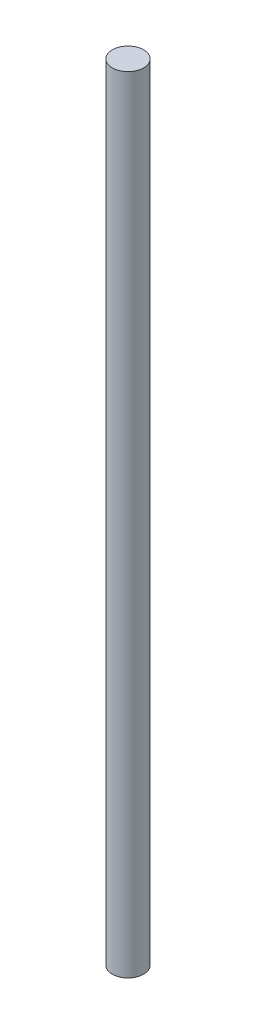
SolidWorks part; units mm, degrees
ref_plane "前视基准面" through (0, 0, 0) normal (0, 0, 1) x (1, 0, 0)
ref_plane "上视基准面" through (0, 0, 0) normal (0, 1, 0) x (1, 0, 0)
ref_plane "右视基准面" through (0, 0, 0) normal (1, 0, 0) x (0, 0, -1)
other "Configuration Table"
sketch "草图1" plane through (0, 0, 0) normal (0, 1, 0) x (1, 0, 0)
  circle A0 centre (0, 0) radius 1.6
  dimension "D1" = 3.2
extrude "凸台-拉伸1" add sketch "草图1" along normal blind 80
